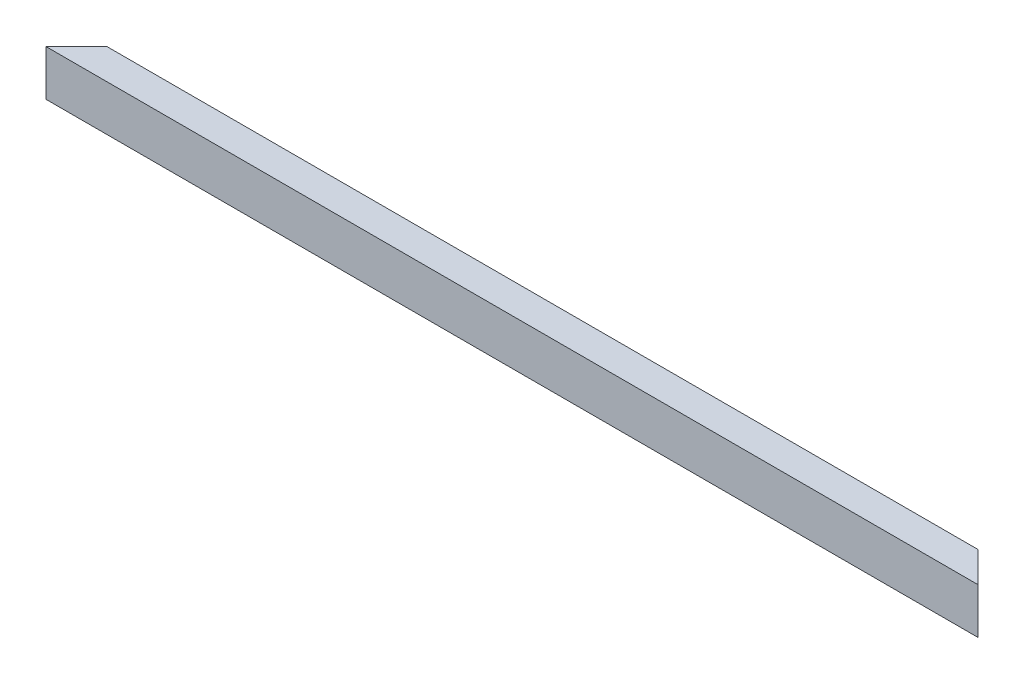
SolidWorks part; units mm, degrees
ref_plane "Front Plane" through (0, 0, 0) normal (0, 0, 1) x (1, 0, 0)
ref_plane "Top Plane" through (0, 0, 0) normal (0, 1, 0) x (1, 0, 0)
ref_plane "Right Plane" through (0, 0, 0) normal (1, 0, 0) x (0, 0, -1)
sketch "Sketch1" plane through (0, 0, 0) normal (0, 1, 0) x (1, 0, 0)
  line L0 (-171.5, 0) -> (171.5, 0)
  line L1 (171.5, 0) -> (183.5, -12)
  line L2 (183.5, -12) -> (-183.5, -12)
  line L3 (0, -12) -> (0, 0)
  line L4 (-171.5, 0) -> (-183.5, -12)
  dimension "D1" = 171.5
  dimension "D2" = 45
  dimension "D3" = 12
extrude "Boss-Extrude1" add sketch "Sketch1" along normal blind 18 contours L3 L2 L1 L0 | L0 L4 L2 L3
sketch "Sketch2" plane through (0, 0, 0) normal (0, 0, -1) x (-1, 0, 0)
  line L0 (-171.5, 15) -> (-187.7229, 15)
  line L1 (171.5, 13) -> (-171.5, 13)
  line L2 (171.5, 15) -> (-171.5, 15)
  line L3 (171.5, 15) -> (-171.5, 15)
  line L4 (-171.5, 15) -> (-148.2432, 15)
  line L5 (-187.7229, 15) -> (-187.7229, 13)
  line L6 (-148.2432, 13) -> (-171.5, 13)
  line L7 (171.5, 15) -> (143.5279, 15)
  line L8 (-187.7229, 13) -> (-171.5, 13)
  line L9 (143.5279, 13) -> (171.5, 13)
  line L10 (171.5, 15) -> (200.2449, 15)
  line L11 (200.2449, 15) -> (200.2449, 13)
  line L12 (200.2449, 13) -> (171.5, 13)
  line L13 (171.5, 13) -> (171.9446, 12.8269)
  line M10 (171.5, 0) -> (171.5, 18)
  line M12 (-171.5, 18) -> (-171.5, 0)
  dimension "D1" = 3
extrude "Cut-Extrude1" cut sketch "Sketch2" against normal blind 3 contours L3 L1 M10 M12 | L12 L11 L10 M10 | L5 L8 L0 M12
